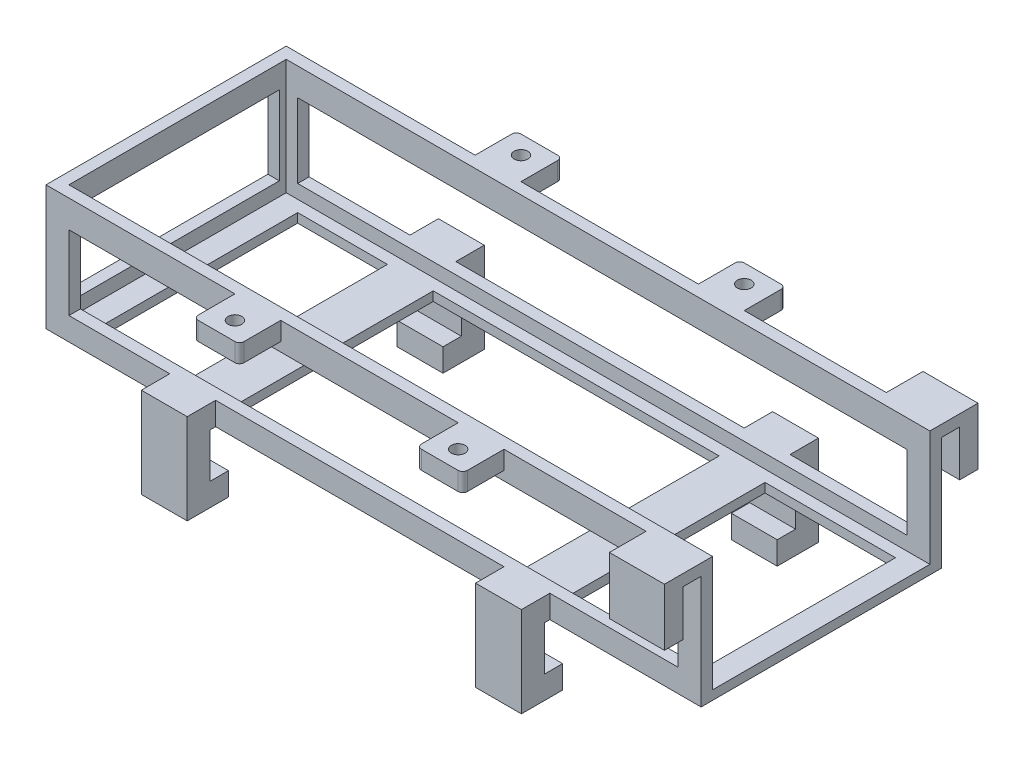
SolidWorks part; units mm, degrees
ref_plane "Front Plane" through (0, 0, 0) normal (0, 0, 1) x (1, 0, 0)
ref_plane "Top Plane" through (0, 0, 0) normal (0, 1, 0) x (1, 0, 0)
ref_plane "Right Plane" through (0, 0, 0) normal (1, 0, 0) x (0, 0, -1)
sketch "Sketch1" plane through (0, 0, 0) normal (0, 1, 0) x (1, 0, 0)
  line L1 (-72.7, -26.2) -> (72.7, -26.2)
  line L2 (-72.7, -26.2) -> (-72.7, 26.2)
  line L3 (-72.7, 26.2) -> (72.7, 26.2)
  line L4 (72.7, -26.2) -> (72.7, 26.2)
  line L5 (-72.7, -26.2) -> (72.7, 26.2) construction
  line L6 (-72.7, 26.2) -> (72.7, -26.2) construction
  point P0 (0, 0)
  dimension "D1" = 145.4
  dimension "D2" = 52.4
extrude "Boss-Extrude1" add sketch "Sketch1" along normal blind 27.2
sketch "Sketch2" plane through (0, 27.2, 0) normal (0, 1, 0) x (1, 0, 0)
  line L1 (-70.2, -23.7) -> (70.2, -23.7)
  line L2 (-70.2, -23.7) -> (-70.2, 23.7)
  line L3 (-70.2, 23.7) -> (70.2, 23.7)
  line L4 (70.2, -23.7) -> (70.2, 23.7)
  line L5 (-70.2, -23.7) -> (70.2, 23.7) construction
  line L6 (-70.2, 23.7) -> (70.2, -23.7) construction
  point P0 (0, 0)
  dimension "D1" = 140.4
  dimension "D2" = 47.4
extrude "Cut-Extrude1" cut sketch "Sketch2" against normal blind 25.2
sketch "Sketch3" plane through (70.2, 0, 0) normal (-1, 0, 0) x (0, 0, 1)
  line L0 (23.7, 2) -> (23.7, 27.2) construction
  line L1 (-22.7, 27.2) -> (23.7, 27.2)
  line L2 (-22.7, 27.2) -> (-22.7, 2)
  line L3 (-22.7, 2) -> (23.7, 2)
  line L4 (23.7, 27.2) -> (23.7, 2)
  line L5 (-22.7, 27.2) -> (23.7, 2) construction
  line L6 (-22.7, 2) -> (23.7, 27.2) construction
  line L7 (23.7, 2) -> (-23.7, 2) construction
  point P0 (0.5, 14.6)
extrude "Cut-Extrude2" cut sketch "Sketch3" against normal blind 25.2
sketch "Sketch8" plane through (0, 27.2, 0) normal (0, 1, 0) x (1, 0, 0)
  line L0 (72.7, 26.2) -> (6, 26.2) construction
  line L1 (72.7, -26.2) -> (70.2, -26.2)
  line L2 (72.7, -26.2) -> (72.7, 26.2)
  line L3 (72.7, 26.2) -> (70.2, 26.2)
  line L4 (70.2, -26.2) -> (70.2, 26.2)
  dimension "D1" = 2.5
extrude "Cut-Extrude5" cut sketch "Sketch8" against normal blind 43
sketch "Sketch9" plane through (-72.7, 0, 0) normal (-1, 0, 0) x (0, 0, 1)
  line L0 (26.2, 27.2) -> (26.2, 0) construction
  line L1 (-22.2, 5) -> (22.2, 5)
  line L2 (-22.2, 5) -> (-22.2, 22.2)
  line L3 (-22.2, 22.2) -> (22.2, 22.2)
  line L4 (22.2, 5) -> (22.2, 22.2)
  line L5 (-22.2, 5) -> (22.2, 22.2) construction
  line L6 (-22.2, 22.2) -> (22.2, 5) construction
  line L7 (-26.2, 27.2) -> (-26.2, 0) construction
  line L8 (-26.2, 27.2) -> (26.2, 27.2) construction
  line L9 (-26.2, 0) -> (26.2, 0) construction
  point P0 (0, 13.6)
  dimension "D1" = 4
  dimension "D2" = 4
  dimension "D3" = 5
  dimension "D4" = 5
extrude "Cut-Extrude6" cut sketch "Sketch9" against normal blind 43
sketch "Sketch11" plane through (0, 0, -26.2) normal (0, 0, -1) x (-1, 0, 0)
  line L0 (-70.2, 0) -> (72.7, 0) construction
  line L1 (-65.2, 21.2) -> (67.7, 21.2)
  line L2 (-65.2, 21.2) -> (-65.2, 5)
  line L3 (-65.2, 5) -> (67.7, 5)
  line L4 (67.7, 21.2) -> (67.7, 5)
  line L5 (-70.2, 0) -> (-70.2, 27.2) construction
  line L6 (72.7, 27.2) -> (72.7, 0) construction
  line L7 (-70.2, 27.2) -> (72.7, 27.2) construction
  dimension "D1" = 5
  dimension "D2" = 5
  dimension "D3" = 5
  dimension "D4" = 6
extrude "Cut-Extrude7" cut sketch "Sketch11" against normal blind 59
sketch "Sketch12" plane through (0, 0, 0) normal (0, -1, 0) x (-1, 0, 0)
  line L0 (-70.2, -26.2) -> (-70.2, 26.2) construction
  line L1 (65.2, 21.2) -> (-65.2, 21.2)
  line L2 (65.2, 21.2) -> (65.2, -21.2)
  line L3 (65.2, -21.2) -> (-65.2, -21.2)
  line L4 (-65.2, 21.2) -> (-65.2, -21.2)
  line L5 (65.2, 21.2) -> (-65.2, -21.2) construction
  line L6 (65.2, -21.2) -> (-65.2, 21.2) construction
  line L7 (-70.2, 26.2) -> (72.7, 26.2) construction
  point P0 (0, 0)
  dimension "D1" = 5
  dimension "D2" = 5
extrude "Cut-Extrude8" cut sketch "Sketch12" against normal blind 10
sketch "Sketch16" plane through (0, 0, -26.2) normal (0, 0, -1) x (-1, 0, 0)
  line L0 (-70.2, 0) -> (-70.2, 27.2) construction
  line L1 (-70.2, 24.7) -> (-58.2, 24.7)
  line L2 (-70.2, 24.7) -> (-70.2, 27.2)
  line L3 (-70.2, 27.2) -> (-58.2, 27.2)
  line L4 (-58.2, 24.7) -> (-58.2, 27.2)
  line L5 (-70.2, 27.2) -> (72.7, 27.2) construction
  dimension "D1" = 12
  dimension "D2" = 2.5
extrude "Boss-Extrude4" add sketch "Sketch16" along normal blind 8
sketch "Sketch18" plane through (0, 0, 26.2) normal (0, 0, 1) x (1, 0, 0)
  line L1 (70.2, 27.2) -> (58.2, 27.2)
  line L2 (70.2, 27.2) -> (70.2, 24.7)
  line L3 (70.2, 24.7) -> (58.2, 24.7)
  line L4 (58.2, 27.2) -> (58.2, 24.7)
  dimension "D1" = 2.5
  dimension "D2" = 12
extrude "Boss-Extrude6" add sketch "Sketch18" along normal blind 8
sketch "Sketch24" plane through (0, 0, 26.2) normal (0, 0, 1) x (1, 0, 0)
  line L0 (-72.7, 0) -> (70.2, 0) construction
  line L1 (-45.7, 0) -> (-35.7, 0)
  line L2 (-45.7, 0) -> (-45.7, 5)
  line L3 (-45.7, 5) -> (-35.7, 5)
  line L4 (-35.7, 0) -> (-35.7, 5)
  line L5 (65.2, 5) -> (-67.7, 5) construction
  line L6 (-72.7, 27.2) -> (-72.7, 0) construction
  line L7 (27.2, 0) -> (37.2, 0)
  line L8 (27.2, 0) -> (27.2, 5)
  line L9 (27.2, 5) -> (37.2, 5)
  line L10 (37.2, 0) -> (37.2, 5)
  line L11 (70.2, 0) -> (70.2, 24.7) construction
  point P14 (-45.7, 2.5)
  point P17 (37.2, 2.5)
  dimension "D1" = 10
  dimension "D2" = 10
  dimension "D3" = 27
  dimension "D4" = 33
extrude "Boss-Extrude12" add sketch "Sketch24" along normal blind 6.2
sketch "Sketch25" plane through (0, 0, -26.2) normal (0, 0, -1) x (-1, 0, 0)
  line L0 (-70.2, 0) -> (72.7, 0) construction
  line L1 (45.7, 0) -> (35.7, 0)
  line L2 (45.7, 0) -> (45.7, 5)
  line L3 (45.7, 5) -> (35.7, 5)
  line L4 (35.7, 0) -> (35.7, 5)
  line L5 (-65.2, 5) -> (67.7, 5) construction
  line L6 (-70.2, 0) -> (-70.2, 24.7) construction
  line L7 (-27.2, 0) -> (-37.2, 0)
  line L8 (-27.2, 0) -> (-27.2, 5)
  line L9 (-27.2, 5) -> (-37.2, 5)
  line L10 (-37.2, 0) -> (-37.2, 5)
  line L11 (72.7, 27.2) -> (72.7, 0) construction
  point P16 (45.7, 2.5)
  dimension "D1" = 10
  dimension "D2" = 10
  dimension "D3" = 33
  dimension "D4" = 27
extrude "Boss-Extrude13" add sketch "Sketch25" along normal blind 6.2
sketch "Sketch26" plane through (0, 0, 0) normal (0, -1, 0) x (-1, 0, 0)
  line L0 (35.7, 32.4) -> (35.7, 26.2) construction
  line L1 (45.7, 32.4) -> (35.7, 32.4)
  line L2 (45.7, 32.4) -> (45.7, 27.4)
  line L3 (45.7, 27.4) -> (35.7, 27.4)
  line L4 (35.7, 32.4) -> (35.7, 27.4)
  line L5 (35.7, -32.4) -> (35.7, -26.2) construction
  line L6 (45.7, -32.4) -> (35.7, -32.4)
  line L7 (45.7, -32.4) -> (45.7, -27.4)
  line L8 (45.7, -27.4) -> (35.7, -27.4)
  line L9 (35.7, -32.4) -> (35.7, -27.4)
  line L10 (-37.2, -32.4) -> (-37.2, -26.2) construction
  line L11 (-27.2, -32.4) -> (-37.2, -32.4)
  line L12 (-27.2, -32.4) -> (-27.2, -27.4)
  line L13 (-27.2, -27.4) -> (-37.2, -27.4)
  line L14 (-37.2, -32.4) -> (-37.2, -27.4)
  line L20 (-37.2, 32.4) -> (-37.2, 26.2) construction
  line L21 (-27.2, 32.4) -> (-37.2, 32.4)
  line L22 (-27.2, 32.4) -> (-27.2, 27.4)
  line L23 (-27.2, 27.4) -> (-37.2, 27.4)
  line L24 (-37.2, 32.4) -> (-37.2, 27.4)
  dimension "D1" = 5
  dimension "D2" = 5
  dimension "D3" = 5
  dimension "D4" = 5
extrude "Boss-Extrude14" add sketch "Sketch26" along normal blind 9.7
sketch "Sketch27" plane through (0, -9.7, 0) normal (0, -1, 0) x (-1, 0, 0)
  line L1 (45.7, -32.4) -> (35.7, -32.4)
  line L2 (45.7, -32.4) -> (45.7, -23.4)
  line L3 (45.7, -23.4) -> (35.7, -23.4)
  line L4 (35.7, -32.4) -> (35.7, -23.4)
  line L5 (-27.2, -32.4) -> (-37.2, -32.4)
  line L6 (-27.2, -32.4) -> (-27.2, -23.4)
  line L7 (-27.2, -23.4) -> (-37.2, -23.4)
  line L8 (-37.2, -32.4) -> (-37.2, -23.4)
  line L9 (45.7, 32.4) -> (35.7, 32.4)
  line L10 (45.7, 32.4) -> (45.7, 23.4)
  line L11 (45.7, 23.4) -> (35.7, 23.4)
  line L12 (35.7, 32.4) -> (35.7, 23.4)
  line L13 (-27.2, 32.4) -> (-37.2, 32.4)
  line L14 (-27.2, 32.4) -> (-27.2, 23.4)
  line L15 (-27.2, 23.4) -> (-37.2, 23.4)
  line L16 (-37.2, 32.4) -> (-37.2, 23.4)
  dimension "D1" = 9
  dimension "D2" = 10
  dimension "D3" = 9
  dimension "D4" = 10
  dimension "D5" = 9
  dimension "D6" = 10
  dimension "D7" = 10
  dimension "D8" = 9
extrude "Boss-Extrude15" add sketch "Sketch27" along normal blind 5
sketch "Sketch28" plane through (0, 0, -21.2) normal (0, 0, 1) x (1, 0, 0)
  line L0 (-65.2, 0) -> (65.2, 0) construction
  line L1 (-45.6292, 0) -> (-35.6292, 0)
  line L2 (-45.6292, 0) -> (-45.6292, 2)
  line L3 (-45.6292, 2) -> (-35.6292, 2)
  line L4 (-35.6292, 0) -> (-35.6292, 2)
  line L5 (-65.2, 2) -> (65.2, 2) construction
  dimension "D1" = 10
extrude "Boss-Extrude16" add sketch "Sketch28" along normal up to vertex (42.4 mm away)
sketch "Sketch29" plane through (0, 0, -21.2) normal (0, 0, 1) x (1, 0, 0)
  line L0 (-35.6292, 0) -> (65.2, 0) construction
  line L1 (26.7424, 0) -> (36.7424, 0)
  line L2 (26.7424, 0) -> (26.7424, 2)
  line L3 (26.7424, 2) -> (36.7424, 2)
  line L4 (36.7424, 0) -> (36.7424, 2)
  line L5 (-35.6292, 2) -> (65.2, 2) construction
  dimension "D1" = 10
extrude "Boss-Extrude17" add sketch "Sketch29" along normal up to vertex (42.4 mm away)
sketch "Sketch30" plane through (0, 24.7, 0) normal (0, -1, 0) x (-1, 0, 0)
  line L0 (-70.2, -34.2) -> (-70.2, -26.2) construction
  line L1 (-58.2, -34.2) -> (-70.2, -34.2)
  line L2 (-58.2, -34.2) -> (-58.2, -30.2)
  line L3 (-58.2, -30.2) -> (-70.2, -30.2)
  line L4 (-70.2, -34.2) -> (-70.2, -30.2)
  line L5 (-70.2, 34.2) -> (-70.2, 26.2) construction
  line L6 (-58.2, 34.2) -> (-70.2, 34.2)
  line L7 (-58.2, 34.2) -> (-58.2, 30.2)
  line L8 (-58.2, 30.2) -> (-70.2, 30.2)
  line L9 (-70.2, 34.2) -> (-70.2, 30.2)
  dimension "D1" = 4
extrude "Boss-Extrude18" add sketch "Sketch30" along normal blind 10
sketch "Sketch35" plane through (0, 0, -26.2) normal (0, 0, -1) x (-1, 0, 0)
  line L0 (-58.2, 27.2) -> (72.7, 27.2) construction
  line L1 (-27.2144, 27.2) -> (-17.2144, 27.2)
  line L2 (-27.2144, 27.2) -> (-27.2144, 21.2)
  line L3 (-27.2144, 21.2) -> (-17.2144, 21.2)
  line L4 (-17.2144, 27.2) -> (-17.2144, 21.2)
  line L5 (67.7, 21.2) -> (-65.2, 21.2) construction
  line L7 (31.4947, 21.2) -> (21.4947, 21.2)
  line L8 (31.4947, 21.2) -> (31.4947, 27.2)
  line L9 (31.4947, 27.2) -> (21.4947, 27.2)
  line L10 (21.4947, 21.2) -> (21.4947, 27.2)
  dimension "D1" = 10
  dimension "D2" = 10
extrude "Boss-Extrude22" add sketch "Sketch35" along normal blind 9
sketch "Sketch36" plane through (0, 0, 26.2) normal (0, 0, 1) x (1, 0, 0)
  line L0 (-67.7, 21.2) -> (65.2, 21.2) construction
  line L1 (-31.49, 21.2) -> (-21.49, 21.2)
  line L2 (-31.49, 21.2) -> (-31.49, 27.2)
  line L3 (-31.49, 27.2) -> (-21.49, 27.2)
  line L4 (-21.49, 21.2) -> (-21.49, 27.2)
  line L5 (-72.7, 27.2) -> (58.2, 27.2) construction
  line L6 (58.2, 27.2) -> (58.2, 24.7) construction
  line L7 (27.21, 21.2) -> (17.21, 21.2)
  line L8 (27.21, 21.2) -> (27.21, 27.2)
  line L9 (27.21, 27.2) -> (17.21, 27.2)
  line L10 (17.21, 21.2) -> (17.21, 27.2)
  line L11 (-72.7, 27.2) -> (-72.7, 0) construction
  point P16 (-31.49, 24.2)
  dimension "D1" = 10
  dimension "D2" = 10
  dimension "D3" = 30.99
  dimension "D4" = 41.21
extrude "Boss-Extrude23" add sketch "Sketch36" along normal blind 9
sketch "Sketch37" plane through (0, 21.2, 0) normal (0, -1, 0) x (1, 0, 0)
  line L0 (-31.49, 35.2) -> (-21.49, 35.2) construction
  line L1 (17.21, 35.2) -> (27.21, 35.2) construction
  line L2 (-21.4947, -35.2) -> (-31.4947, -35.2) construction
  line L3 (27.2144, -35.2) -> (17.2144, -35.2) construction
  circle A0 centre (-26.49, 31.2) radius 1.5
  circle A1 centre (22.21, 31.2) radius 1.5
  circle A2 centre (-26.49, -31.2) radius 1.5
  circle A3 centre (22.2144, -31.2) radius 1.5
  dimension "D1" = 3
  dimension "D2" = 3
  dimension "D3" = 3
  dimension "D4" = 3
  dimension "D6" = 4
  dimension "D7" = 4
  dimension "D5" = 4
  dimension "D8" = 4
extrude "Cut-Extrude10" cut sketch "Sketch37" against normal blind 9
sketch "Sketch38" plane through (0, 0, 35.2) normal (0, 0, 1) x (1, 0, 0)
  line L0 (-21.49, 21.2) -> (-21.49, 27.2) construction
  line L1 (-31.49, 21.2) -> (-21.49, 21.2)
  line L2 (-31.49, 21.2) -> (-31.49, 23.2)
  line L3 (-31.49, 23.2) -> (-21.49, 23.2)
  line L4 (-21.49, 21.2) -> (-21.49, 23.2)
  dimension "D1" = 2
extrude "Cut-Extrude11" cut sketch "Sketch38" against normal blind 9
sketch "Sketch39" plane through (0, 0, 35.2) normal (0, 0, 1) x (1, 0, 0)
  line L0 (27.21, 21.2) -> (27.21, 27.2) construction
  line L1 (17.21, 21.2) -> (27.21, 21.2)
  line L2 (17.21, 21.2) -> (17.21, 23.2)
  line L3 (17.21, 23.2) -> (27.21, 23.2)
  line L4 (27.21, 21.2) -> (27.21, 23.2)
  dimension "D1" = 2
extrude "Cut-Extrude12" cut sketch "Sketch39" against normal blind 9
sketch "Sketch40" plane through (0, 0, -35.2) normal (0, 0, -1) x (-1, 0, 0)
  line L0 (-17.2144, 21.2) -> (-17.2144, 27.2) construction
  line L1 (-27.2144, 21.2) -> (-17.2144, 21.2)
  line L2 (-27.2144, 21.2) -> (-27.2144, 23.2)
  line L3 (-27.2144, 23.2) -> (-17.2144, 23.2)
  line L4 (-17.2144, 21.2) -> (-17.2144, 23.2)
  line L5 (31.4947, 21.2) -> (31.4947, 27.2) construction
  line L6 (21.4947, 21.2) -> (31.4947, 21.2)
  line L7 (21.4947, 21.2) -> (21.4947, 23.2)
  line L8 (21.4947, 23.2) -> (31.4947, 23.2)
  line L9 (31.4947, 21.2) -> (31.4947, 23.2)
  dimension "D1" = 2
  dimension "D2" = 2
extrude "Cut-Extrude13" cut sketch "Sketch40" against normal blind 9
fillet "Fillet1" radius 1 8 edges at (27.21, 25.2, 35.2) (17.21, 25.2, 35.2) (-21.49, 25.2, 35.2) (-31.49, 25.2, 35.2) (27.2144, 25.2, -35.2) (17.2144, 25.2, -35.2) (-21.4947, 25.2, -35.2) (-31.4947, 25.2, -35.2)
